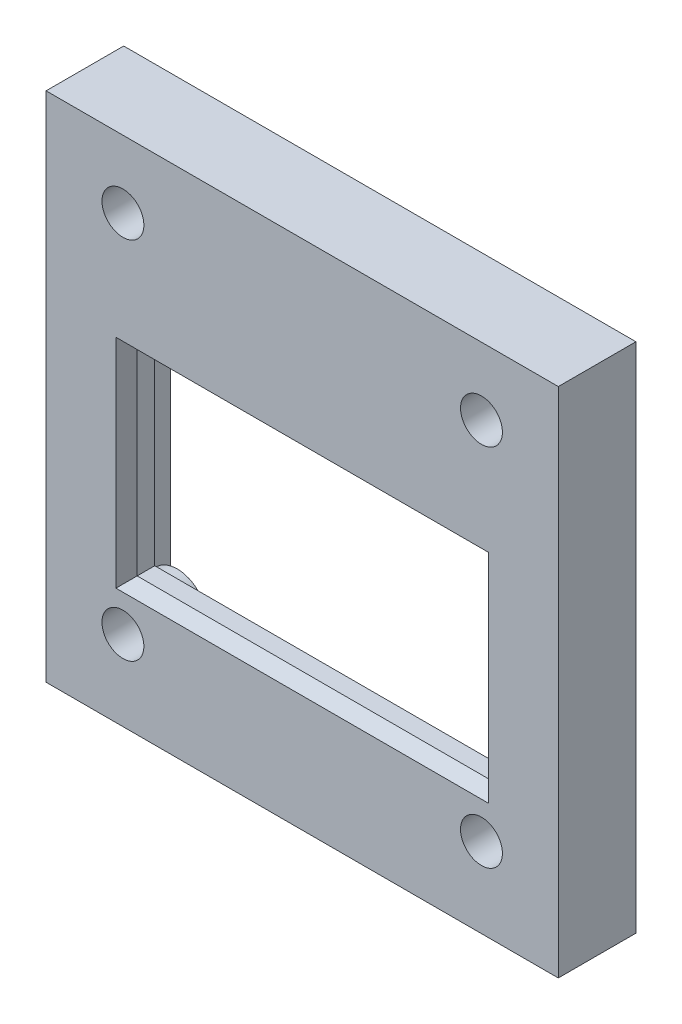
SolidWorks part; units mm, degrees
ref_plane "Front Plane" through (0, 0, 0) normal (0, 0, 1) x (1, 0, 0)
ref_plane "Top Plane" through (0, 0, 0) normal (0, 1, 0) x (1, 0, 0)
ref_plane "Right Plane" through (0, 0, 0) normal (1, 0, 0) x (0, 0, -1)
sketch "Sketch1" plane through (0, 0, 0) normal (0, 0, 1) x (1, 0, 0)
  line L5 (-17.1, -14.575) -> (15.9, -14.575)
  line L6 (-17.1, -14.575) -> (-17.1, 18.425)
  line L7 (10.9, -6.575) -> (-12.1, -6.575)
  line L8 (10.9, -6.575) -> (10.9, 6.425)
  line L9 (10.9, 6.425) -> (-12.1, 6.425)
  line L10 (-12.1, -6.575) -> (-12.1, 6.425)
  line L11 (10.9, -6.575) -> (-12.1, 6.425) construction
  line L12 (10.9, 6.425) -> (-12.1, -6.575) construction
  line L13 (-17.1, 18.425) -> (15.9, 18.425)
  line L14 (15.9, -14.575) -> (15.9, 18.425)
  line L15 (-17.1, -14.575) -> (15.9, 18.425) construction
  line L16 (-17.1, 18.425) -> (15.9, -14.575) construction
  point P0 (0, 0)
  point P1 (-0.6, 1.925)
  point P6 (-0.6, -0.075)
  dimension "D1" = 5
  dimension "D2" = 5
  dimension "D3" = 12
  dimension "D4" = 33
  dimension "D5" = 33
  dimension "D6" = 8
extrude "Boss-Extrude1" add sketch "Sketch1" along normal blind 2
chamfer "Chamfer1" distance 0.5 angle 60 4 edges at (10.9, -0.075, 2) (-0.6, -6.575, 2) (-12.1, -0.075, 2) (-0.6, 6.425, 2)
sketch "Sketch2" plane through (0, 0, 0) normal (0, 0, -1) x (-1, 0, 0)
  line L1 (-15.9, 18.425) -> (17.1, 18.425)
  line L2 (-15.9, 18.425) -> (-15.9, -14.575)
  line L3 (-15.9, -14.575) -> (17.1, -14.575)
  line L4 (17.1, 18.425) -> (17.1, -14.575)
  line L5 (-12.9, 16.075) -> (14.1, 16.075)
  line L6 (-12.9, 16.075) -> (-12.9, -12.075)
  line L7 (-12.9, -12.075) -> (14.1, -12.075)
  line L8 (14.1, 16.075) -> (14.1, -12.075)
  dimension "D1" = 3
  dimension "D2" = 2.35
  dimension "D3" = 2.5
  dimension "D4" = 3
extrude "Boss-Extrude2" add sketch "Sketch2" along normal blind 3
sketch "Sketch3" plane through (0, 0, 0) normal (0, 0, -1) x (-1, 0, 0)
  line L1 (-10.95, 14.075) -> (12.15, 14.075)
  line L2 (-10.95, 14.075) -> (-10.95, -9.425)
  line L3 (-10.95, -9.425) -> (12.15, -9.425)
  line L4 (12.15, 14.075) -> (12.15, -9.425)
  line L7 (-15.9, 18.425) -> (-15.9, -14.575) construction
  line L8 (17.1, 18.425) -> (-15.9, 18.425) construction
  circle A0 centre (-10.95, 14.075) radius 1.35
  circle A1 centre (12.15, 14.075) radius 1.35
  circle A2 centre (12.15, -9.425) radius 1.35
  circle A3 centre (-10.95, -9.425) radius 1.35
  dimension "2.2" = 2.7
  dimension "D4" = 4.35
  dimension "D1" = 23.1
  dimension "D2" = 23.5
  dimension "D3" = 4.95
extrude "Cut-Extrude2" cut sketch "Sketch3" against normal blind 3 contours L1 A0 L2 | L2 A0 L1 | L4 A1 L1 | L1 A1 L4 | L3 A2 L4 | L2 A3 L3 | L3 A3 L2
sketch "Sketch4" plane through (0, 0, 0) normal (0, 0, -1) x (-1, 0, 0)
  circle A0 centre (-10.95, 14.075) radius 1.1
  circle A1 centre (12.15, 14.075) radius 1.1
  circle A2 centre (-10.95, -9.425) radius 1.1
  circle A3 centre (12.15, -9.425) radius 1.1
  circle A4 centre (-10.95, 14.075) radius 1.9
  circle A5 centre (12.15, 14.075) radius 1.9
  circle A6 centre (-10.95, -9.425) radius 1.9
  circle A7 centre (12.15, -9.425) radius 1.9
  dimension "D1" = 0.8
extrude "Boss-Extrude3" add sketch "Sketch4" along normal blind 1.5
sketch "Sketch5" plane through (0, 0, 2) normal (0, 0, 1) x (1, 0, 0)
  circle A0 centre (-12.15, 14.075) radius 1.35
  circle A1 centre (10.95, 14.075) radius 1.35
  circle A2 centre (-12.15, -9.425) radius 1.35
  circle A3 centre (10.95, -9.425) radius 1.35
extrude "Cut-Extrude3" cut sketch "Sketch5" against normal blind 10
sketch "Sketch6" plane through (0, 0, -3) normal (0, 0, -1) x (-1, 0, 0)
  line L0 (-12.9, -12.075) -> (14.1, -12.075) construction
  line L1 (-6.9, -12.075) -> (8.1, -12.075)
  line L2 (-6.9, -12.075) -> (-6.9, -13.575)
  line L3 (-6.9, -13.575) -> (8.1, -13.575)
  line L4 (8.1, -12.075) -> (8.1, -13.575)
  line L5 (0.6, -12.075) -> (0.6, -13.575) construction
  line L6 (14.1, 16.075) -> (-12.9, 16.075) construction
  line L7 (17.1, 18.425) -> (-15.9, 18.425) construction
  point P10 (0, 0)
  point P11 (0.6, 16.075)
  point P12 (0, 0)
  point P13 (0.6, 18.425)
  dimension "D1" = 1.5
  dimension "D2" = 15
extrude "Cut-Extrude4" cut sketch "Sketch6" against normal up to surface (3 mm away) up to face at (-14.05, -9.425, 0)
